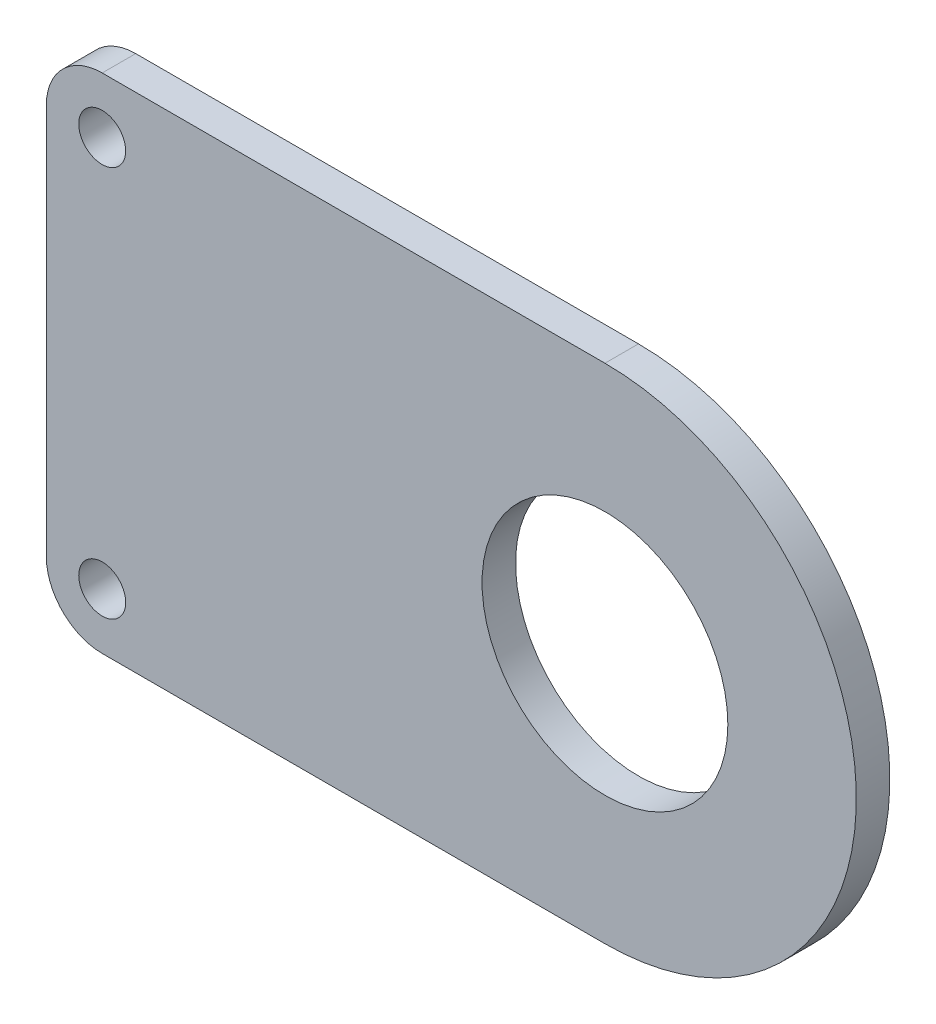
SolidWorks part; units mm, degrees
material "5052-H34"
ref_plane "正面" through (0, 0, 0) normal (0, 0, 1) x (1, 0, 0)
ref_plane "平面" through (0, 0, 0) normal (0, 1, 0) x (1, 0, 0)
ref_plane "右側面" through (0, 0, 0) normal (1, 0, 0) x (0, 0, -1)
sketch "ｽｹｯﾁ1" plane through (0, 0, 0) normal (0, 0, 1) x (1, 0, 0)
  line L0 (0, 0) -> (-45, 0) construction
  line L1 (-45, 0) -> (-45, 17.5) construction
  line L2 (-40, 22.5) -> (0, 22.5)
  line L3 (-50, 22.5) -> (-40, 22.5)
  line L4 (-50, 22.5) -> (-50, -22.5)
  line L5 (-50, -22.5) -> (-40, -22.5)
  line L6 (-40, 22.5) -> (-40, 0) construction
  line L7 (-50, 22.5) -> (-40, -22.5) construction
  line L8 (-50, -22.5) -> (-40, 22.5) construction
  line L9 (-40, -22.5) -> (0, -22.5)
  line L10 (-40, 0) -> (-40, -22.5) construction
  circle A0 centre (0, 0) radius 11
  circle A1 centre (-45, 17.5) radius 2.1
  circle A2 centre (-45, -17.5) radius 2.1
  arc A3 (0, -22.5) -> (0, 22.5) centre (0, 0) ccw
  arc A4 (0, 22.5) -> (-22.5, 0) centre (0, 0) ccw construction
  arc A5 (-22.5, 0) -> (0, -22.5) centre (0, 0) ccw construction
  dimension "D1" = 22
  dimension "D2" = 4.2
  dimension "D5" = 45
  dimension "D3" = 35
  dimension "D4" = 45
  dimension "D6" = 10
extrude "ﾎﾞｽ - 押し出し1" add sketch "ｽｹｯﾁ1" along normal blind 3
fillet "ﾌｨﾚｯﾄ1" radius 5 2 edges at (-50, -22.5, 1.5) (-50, 22.5, 1.5)
